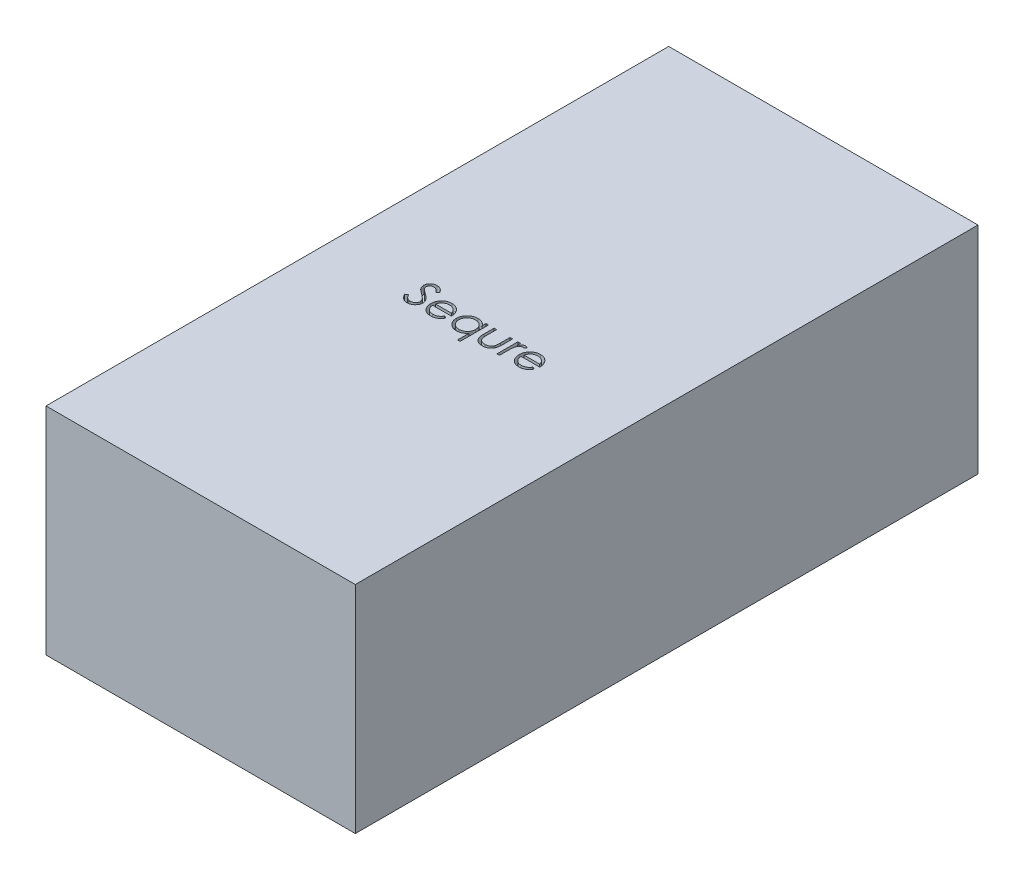
SolidWorks part; units mm, degrees
ref_plane "Front Plane" through (0, 0, 0) normal (0, 0, 1) x (1, 0, 0)
ref_plane "Top Plane" through (0, 0, 0) normal (0, 1, 0) x (1, 0, 0)
ref_plane "Right Plane" through (0, 0, 0) normal (1, 0, 0) x (0, 0, -1)
sketch "Sketch1" plane through (0, 0, 0) normal (0, 1, 0) x (1, 0, 0)
  line L1 (0, 0) -> (38, 0)
  line L2 (0, 0) -> (0, 76.5)
  line L3 (0, 76.5) -> (38, 76.5)
  line L4 (38, 0) -> (38, 76.5)
  dimension "D1" = 76.5
  dimension "D2" = 38
extrude "Boss-Extrude1" add sketch "Sketch1" along normal blind 26.5
sketch "Sketch2" plane through (0, 26.5, 0) normal (0, 1, 0) x (1, 0, 0)
  text T0 "Sequre"
extrude "Cut-Extrude1" cut sketch "Sketch2" against normal blind 1
